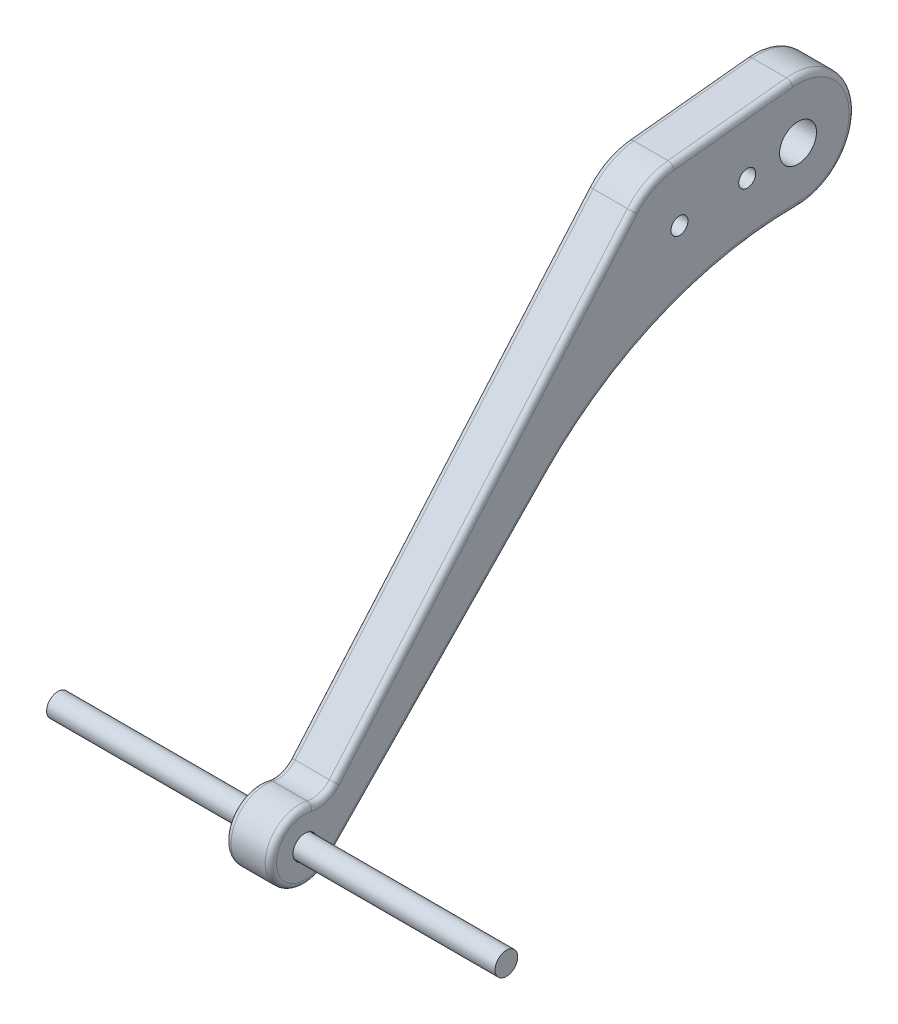
SolidWorks part; units mm, degrees
material "ABS"
ref_plane "Front" through (0, 0, 0) normal (0, 0, 1) x (1, 0, 0)
ref_plane "Top" through (0, 0, 0) normal (0, 1, 0) x (1, 0, 0)
ref_plane "Right" through (0, 0, 0) normal (1, 0, 0) x (0, 0, -1)
sketch "Esquisse3" plane through (0, 0, 0) normal (1, 0, 0) x (0, 0, -1)
  line L1 (-78, 11) -> (-24, 11) construction
  line L2 (-24, 11) -> (-15, -104) construction
  line L3 (-15, -104) -> (-87, -104) construction
  line L4 (-87, -104) -> (-78, 11) construction
  circle A0 centre (-86.8787, -64) radius 2
  circle A1 centre (0, -71.5) radius 60 construction
  circle A2 centre (0, 0) radius 105.907 construction
  point P10 (-51, -104)
  point P11 (-51, 11)
  dimension "D1" = 4
  dimension "D2" = 60
  dimension "D3" = 115
  dimension "D7" = 71.5
  dimension "D9" = 40
  dimension "D10" = 3
  dimension "D11" = 107.907
  dimension "D4" = 54
  dimension "D5" = 72
  dimension "D6" = 82.5
  dimension "D8" = 51
extrude "Boss.-Extru.1" add sketch "Esquisse3" along normal mid plane 79 separate body
sketch "Esquisse5" plane through (0, 0, 0) normal (1, 0, 0) x (0, 0, -1)
  line L0 (-83.47, -59.0623) -> (-29.0836, 4.0082)
  line L1 (-21.9302, 7.7501) -> (-1.0453, 9.9452)
  line L2 (50, 0) -> (-50, 0) construction
  line L4 (-44.0799, -28.6139) -> (-82.5783, -68.184)
  line L5 (-20.885, -2.1951) -> (0, 0) construction
  arc A0 (-83.47, -59.0623) -> (-82.5783, -68.184) centre (-86.8787, -64) ccw
  circle A1 centre (0, 0) radius 3.25
  circle A2 centre (-86.8787, -64) radius 2 construction
  circle A3 centre (-86.8787, -64) radius 2.1
  arc A4 (0, -10) -> (-1.0453, 9.9452) centre (0, 0) ccw
  arc A5 (-29.0836, 4.0082) -> (-21.9302, 7.7501) centre (-20.7848, -3.148) cw
  arc A6 (0, -10) -> (-44.0799, -28.6139) centre (0, -71.5) ccw
  circle A7 centre (0, -71.5) radius 60 construction
  circle A8 centre (-8.9507, -0.9408) radius 1.5
  circle A9 centre (-20.885, -2.1951) radius 1.5
  point P15 (-12.8624, 4.9976)
  point P23 (0, 0)
  point P24 (-23.4643, 9)
  point P25 (-20, 2.8231)
  point P26 (-22.6223, 1.5826)
  point P27 (-36.7399, 2.077)
  point P28 (-53.4808, -14.1092)
  point P29 (-32.798, -2.5878)
  point P30 (-18.1935, 6.2116)
  point P31 (-34.9252, -5.2963)
  point P32 (-20.8757, -1.2501)
  point P33 (0, 0)
  point P34 (-20.5739, -4.0916)
  dimension "D1" = 4.2
  dimension "D2" = 6.5
  dimension "D3" = 20
  dimension "D4" = 12
  dimension "D5" = 3.9
  dimension "D6" = 7
  dimension "D7" = 12
  dimension "D8" = 3
  dimension "D9" = 12
  dimension "D10" = 21
  dimension "D11" = 6
  dimension "D12" = 10.9581
extrude "Boss.-Extru.2" add sketch "Esquisse5" along normal mid plane 8 separate body
fillet "Congé1" radius 4 1 edges at (0, -59.0623, 83.47)
fillet "Congé2" radius 1 16 edges at (-4, 6.5619, 25.8641) (-4, 8.8477, 11.4878) (-4, 0.5234, -9.9863) (-4, -14.8443, 23.9244) (-4, -48.399, 63.3291) (-4, -65.688, 92.6364) (-4, -58.0634, 83.371) (4, 6.5619, 25.8641) (4, 8.8477, 11.4878) (4, 0.5234, -9.9863) (4, -14.8443, 23.9244) (4, -48.399, 63.3291) (4, -65.688, 92.6364) (4, -58.0634, 83.371) (-4, -26.4323, 55.3327) (4, -26.4323, 55.3327)
sketch "Esquisse6" plane through (-4, 0, 0) normal (-1, 0, 0) x (0, 0, 1)
  line L0 (0, 0) -> (19.8904, -2.0906) construction
  line L1 (0.6794, 6.4644) -> (20.5699, 4.3738)
  line L2 (-0.6794, -6.4644) -> (19.211, -8.555)
  arc A0 (0.6794, 6.4644) -> (-0.6794, -6.4644) centre (0, 0) ccw
  arc A1 (19.211, -8.555) -> (20.5699, 4.3738) centre (19.8904, -2.0906) ccw
  circle A2 centre (20.885, -2.1951) radius 1.5 construction
  point P3 (9.9452, -1.0453)
  point P8 (20.885, -2.1951)
  point P9 (0, 0)
  point P12 (0, 0)
  dimension "D1" = 20
  dimension "D2" = 13
extrude "Enlèv. mat.-Extru.1" cut sketch "Esquisse6" against normal blind 3
mirror "Symétrie1" [suppressed] about plane through (0, 0, 0) normal (1, 0, 0)
delete or keep bodies "Corps-Supprimer/Garder 1" [suppressed] type delete bodies bodies 105
